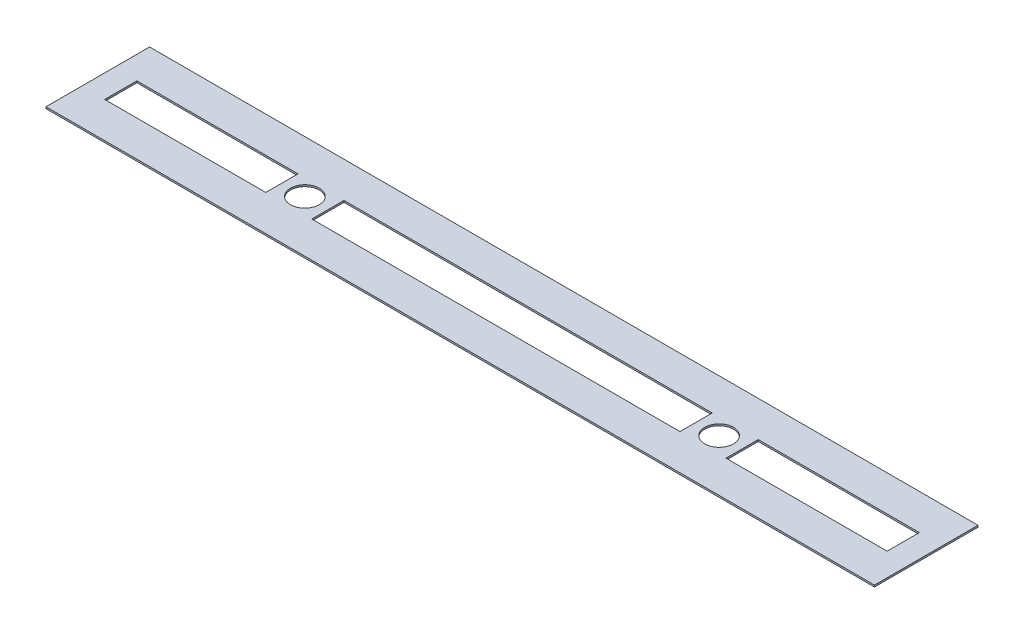
SolidWorks part; units mm, degrees
ref_plane "Front Plane" through (0, 0, 0) normal (0, 0, 1) x (1, 0, 0)
ref_plane "Top Plane" through (0, 0, 0) normal (0, 1, 0) x (1, 0, 0)
ref_plane "Right Plane" through (0, 0, 0) normal (1, 0, 0) x (0, 0, -1)
sketch "Sketch1" plane through (0, 0, 0) normal (0, 1, 0) x (1, 0, 0)
  line L0 (0, 19.71) -> (0, -15.39) construction
  line L1 (-43.875, 0) -> (40.095, 0) construction
  line L2 (20, 1.4) -> (20, -1.4)
  line L3 (-36, 4.5) -> (36, 4.5)
  line L4 (-36, 4.5) -> (-36, -4.5)
  line L5 (-36, -4.5) -> (36, -4.5)
  line L6 (36, 4.5) -> (36, -4.5)
  line L7 (-16, 1.4) -> (16, 1.4)
  line L8 (-16, 1.4) -> (-16, -1.4)
  line L9 (-16, -1.4) -> (16, -1.4)
  line L10 (16, 1.4) -> (16, -1.4)
  line L11 (-34, 1.4) -> (-20, 1.4)
  line L12 (-34, 1.4) -> (-34, -1.4)
  line L13 (-34, -1.4) -> (-20, -1.4)
  line L14 (-20, 1.4) -> (-20, -1.4)
  line L15 (34, -1.4) -> (20, -1.4)
  line L16 (34, 1.4) -> (34, -1.4)
  line L17 (34, 1.4) -> (20, 1.4)
  circle A0 centre (-18, 0) radius 1.25
  circle A1 centre (18, 0) radius 1.25
  dimension "D3" = 2.5
  dimension "D1" = 9
  dimension "D2" = 72
  dimension "D4" = 2.8
  dimension "D5" = 32
  dimension "D6" = 36
  dimension "D7" = 14
  dimension "D8" = 4
extrude "Boss-Extrude1" add sketch "Sketch1" along normal blind 0.15
